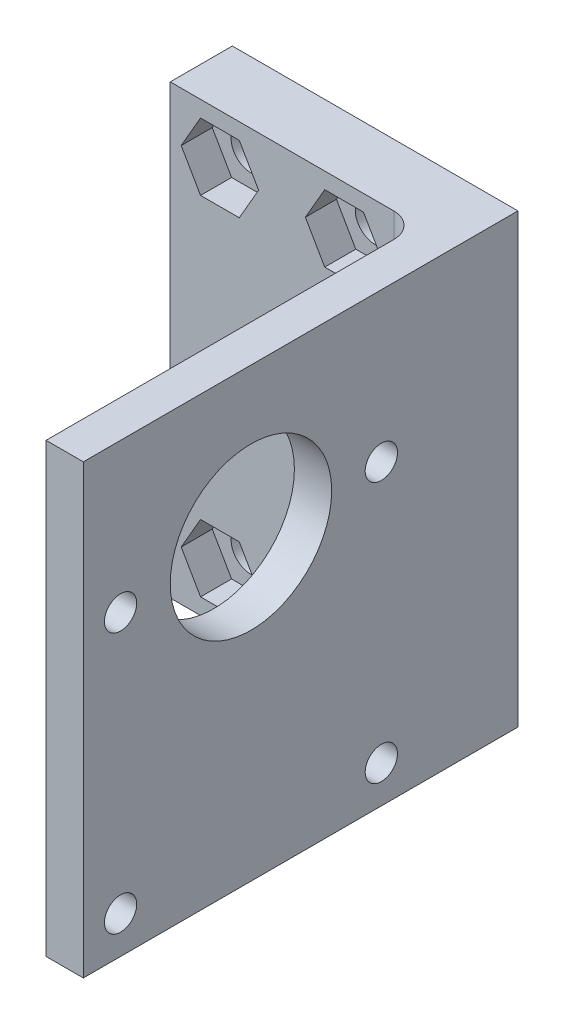
SolidWorks part; units mm, degrees
other "ﾏｰｸｱｯﾌﾟ1"
sketch "ｽｹｯﾁ3" plane through (0, 17.5273, 13.1455) normal (0.7882, 0.0329, 0.6145) x (0.6151, -0.0085, -0.7884)
ref_plane "正面" through (0, 0, 0) normal (0, 0, 1) x (1, 0, 0)
ref_plane "平面" through (0, 0, 0) normal (0, 1, 0) x (1, 0, 0)
ref_plane "右側面" through (0, 0, 0) normal (1, 0, 0) x (0, 0, -1)
sketch "ｽｹｯﾁ2" plane through (0, 0, 0) normal (1, 0, 0) x (0, 0, -1)
  line L0 (-4, -18.7016) -> (-4, 20.3869) construction
  line L1 (-17.5, 18) -> (17.5, 18)
  line L2 (-17.5, 18) -> (-17.5, -18)
  line L3 (-17.5, -18) -> (17.5, -18)
  line L4 (17.5, 18) -> (17.5, -18)
  line L5 (-17.5, 18) -> (17.5, -18) construction
  line L6 (-17.5, -18) -> (17.5, 18) construction
  line L7 (-14.5, 6) -> (6.5, 6) construction
  line L8 (-14.5, 6) -> (-14.5, -15) construction
  line L9 (-14.5, -15) -> (6.5, -15) construction
  line L10 (6.5, 6) -> (6.5, -15) construction
  line L11 (-14.5, 6) -> (6.5, -15) construction
  line L12 (-14.5, -15) -> (6.5, 6) construction
  circle A0 centre (-14.5, 6) radius 1.3
  circle A1 centre (6.5, 6) radius 1.3
  circle A2 centre (-14.5, -15) radius 1.3
  circle A3 centre (6.5, -15) radius 1.3
  circle A4 centre (-4, 6) radius 6.5
  point P0 (0, 0)
  point P6 (0, 0)
  point P11 (-4, -4.5)
  dimension "D5" = 3
  dimension "D6" = 3
  dimension "D7" = 2.6
  dimension "D8" = 2.6
  dimension "D9" = 2.6
  dimension "D10" = 2.6
  dimension "D11" = 13
  dimension "D1" = 35
  dimension "D2" = 36
  dimension "D3" = 21
  dimension "D4" = 21
extrude "ﾎﾞｽ - 押し出し1" add sketch "ｽｹｯﾁ2" along normal blind 3
sketch "ｽｹｯﾁ4" plane through (0, 0, 0) normal (-1, 0, 0) x (0, 0, 1)
  line L0 (17.5, -18) -> (-17.5, -18) construction
  line L1 (-17.5, 18) -> (-12.5, 18)
  line L2 (-17.5, 18) -> (-17.5, -18)
  line L3 (-17.5, -18) -> (-12.5, -18)
  line L4 (-12.5, 18) -> (-12.5, -18)
  dimension "D1" = 5
extrude "ﾎﾞｽ - 押し出し2" add sketch "ｽｹｯﾁ4" along normal blind 20
fillet "ﾌｨﾚｯﾄ1" radius 2 1 edges at (0, 0, -12.5)
sketch "ｽｹｯﾁ5" plane through (0, 0, -12.5) normal (0, 0, 1) x (1, 0, 0)
  line L0 (-2, -18) -> (-2, 18) construction
  line L1 (-12.8823, 14) -> (-14.4412, 16.7)
  line L2 (-14.4412, 16.7) -> (-17.5588, 16.7)
  line L3 (-17.5588, 16.7) -> (-19.1177, 14)
  line L4 (-19.1177, 14) -> (-17.5588, 11.3)
  line L5 (-17.5588, 11.3) -> (-14.4412, 11.3)
  line L6 (-14.4412, 11.3) -> (-12.8823, 14)
  line L7 (-2.8823, 14) -> (-4.4412, 16.7)
  line L8 (-4.4412, 16.7) -> (-7.5588, 16.7)
  line L9 (-7.5588, 16.7) -> (-9.1177, 14)
  line L10 (-9.1177, 14) -> (-7.5588, 11.3)
  line L11 (-7.5588, 11.3) -> (-4.4412, 11.3)
  line L12 (-4.4412, 11.3) -> (-2.8823, 14)
  line L13 (-12.8823, -14) -> (-14.4412, -11.3)
  line L14 (-14.4412, -11.3) -> (-17.5588, -11.3)
  line L15 (-17.5588, -11.3) -> (-19.1177, -14)
  line L16 (-19.1177, -14) -> (-17.5588, -16.7)
  line L17 (-17.5588, -16.7) -> (-14.4412, -16.7)
  line L18 (-14.4412, -16.7) -> (-12.8823, -14)
  line L19 (-2.8823, -14) -> (-4.4412, -11.3)
  line L20 (-4.4412, -11.3) -> (-7.5588, -11.3)
  line L21 (-7.5588, -11.3) -> (-9.1177, -14)
  line L22 (-9.1177, -14) -> (-7.5588, -16.7)
  line L23 (-7.5588, -16.7) -> (-4.4412, -16.7)
  line L24 (-4.4412, -16.7) -> (-2.8823, -14)
  line L25 (-20, -18) -> (-20, 18) construction
  line L26 (-20, 18) -> (-2, 18) construction
  line L27 (-20, -18) -> (-2, -18) construction
  circle A0 centre (-16, 14) radius 2.7 construction
  circle A1 centre (-6, 14) radius 2.7 construction
  circle A2 centre (-16, -14) radius 2.7 construction
  circle A3 centre (-6, -14) radius 2.7 construction
  dimension "D1" = 5.4
  dimension "D2" = 5.4
  dimension "D3" = 5.4
  dimension "D4" = 5.4
  dimension "D5" = 4
  dimension "D6" = 4
  dimension "D7" = 4
  dimension "D8" = 4
  dimension "D9" = 4
  dimension "D10" = 4
  dimension "D11" = 4
  dimension "D12" = 4
extrude "ｶｯﾄ - 押し出し1" cut sketch "ｽｹｯﾁ5" against normal blind 2.5
sketch "ｽｹｯﾁ7" plane through (0, 0, -15) normal (0, 0, 1) x (1, 0, 0)
  line L0 (-20, -18) -> (-2, -18) construction
  line L1 (-20, -18) -> (-20, 18) construction
  line L2 (-2, -18) -> (-2, 18) construction
  line L3 (-20, 18) -> (-2, 18) construction
  circle A0 centre (-16, 14) radius 1.6
  circle A1 centre (-6, 14) radius 1.6
  circle A2 centre (-16, -14) radius 1.6
  circle A3 centre (-6, -14) radius 1.6
  dimension "D1" = 3.2
  dimension "D2" = 3.2
  dimension "D3" = 3.2
  dimension "D4" = 3.2
  dimension "D5" = 4
  dimension "D6" = 4
  dimension "D7" = 4
  dimension "D8" = 4
  dimension "D9" = 4
  dimension "D10" = 4
  dimension "D11" = 4
  dimension "D12" = 4
extrude "ｶｯﾄ - 押し出し2" cut sketch "ｽｹｯﾁ7" against normal blind 10
